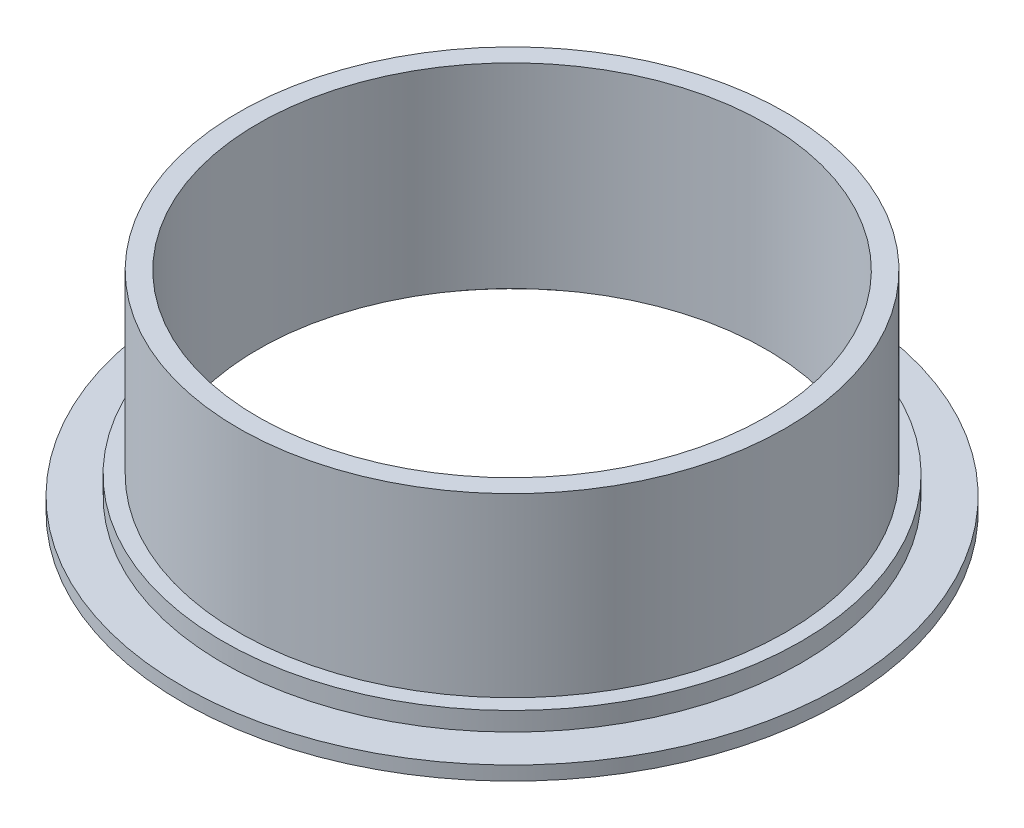
SolidWorks part; units mm, degrees
ref_plane "Front Plane" through (0, 0, 0) normal (0, 0, 1) x (1, 0, 0)
ref_plane "Top Plane" through (0, 0, 0) normal (0, 1, 0) x (1, 0, 0)
ref_plane "Right Plane" through (0, 0, 0) normal (1, 0, 0) x (0, 0, -1)
sketch "Sketch1" plane through (0, 0, 0) normal (0, 0, 1) x (1, 0, 0)
  line L0 (0, -8382.8405) -> (0, 410759.1858) construction
  line L1 (-650, 535.7579) -> (-650, 35.7579)
  line L2 (-650, 35.7579) -> (-700, 35.7579)
  line L3 (-700, 35.7579) -> (-700, 0)
  line L4 (-700, 0) -> (-740, 0)
  line L5 (-650, 535.7579) -> (-700, 535.7579)
  line L6 (-700, 535.7579) -> (-700, 83.6331)
  line L7 (-700, 83.6331) -> (-740, 83.6331)
  line L8 (-740, 83.6331) -> (-740, 35.7579)
  line L9 (-740, 35.7579) -> (-843.1705, 35.7579)
  line L10 (-843.1705, 35.7579) -> (-843.1705, 0)
  line L11 (-843.1705, 0) -> (-740, 0)
  dimension "D1" = 650
  dimension "D2" = 700
  dimension "D3" = 740
  dimension "D4" = 500
  dimension "D6" = 50
revolve "Revolve1" add sketch "Sketch1" angle 360 about L0
